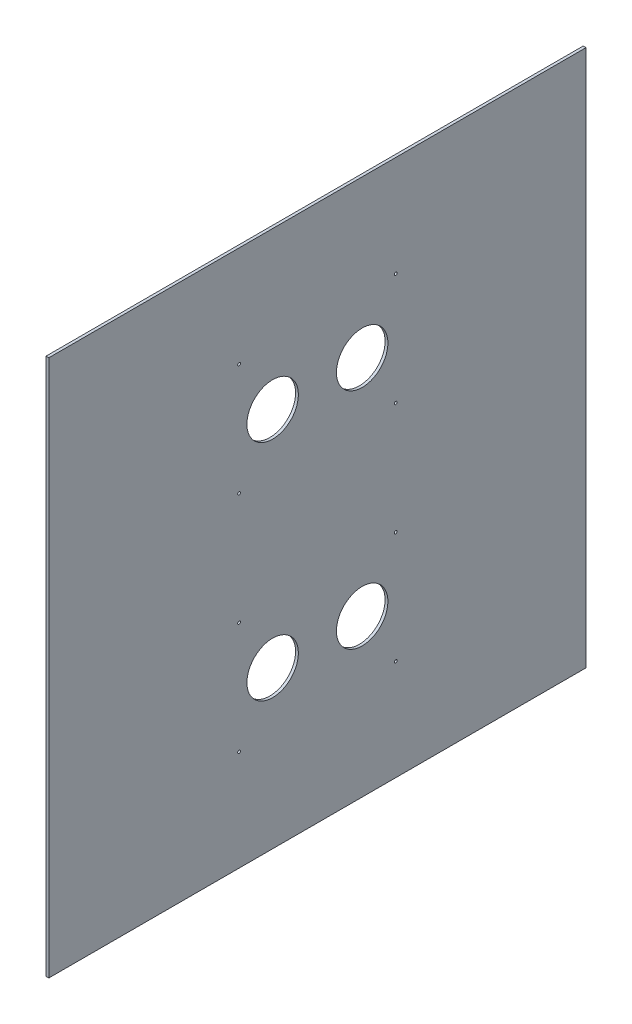
SolidWorks part; units mm, degrees
ref_plane "Front Plane" through (0, 0, 0) normal (0, 0, 1) x (1, 0, 0)
ref_plane "Top Plane" through (0, 0, 0) normal (0, 1, 0) x (1, 0, 0)
ref_plane "Right Plane" through (0, 0, 0) normal (1, 0, 0) x (0, 0, -1)
sketch "Sketch1" plane through (0, 0, 0) normal (1, 0, 0) x (0, 0, -1)
  line L1 (304.8, -304.8) -> (-304.8, -304.8)
  line L2 (304.8, -304.8) -> (304.8, 304.8)
  line L3 (304.8, 304.8) -> (-304.8, 304.8)
  line L4 (-304.8, -304.8) -> (-304.8, 304.8)
  line L5 (304.8, -304.8) -> (-304.8, 304.8) construction
  line L6 (304.8, 304.8) -> (-304.8, -304.8) construction
  point P0 (0, 0)
  dimension "D1" = 609.6
  dimension "D2" = 609.6
extrude "Boss-Extrude1" add sketch "Sketch1" along normal blind 3.175
sketch "Sketch2" plane through (3.175, 0, 0) normal (1, 0, 0) x (0, 0, -1)
  line L0 (-304.8, -304.8) -> (304.8, -304.8) construction
  line L1 (-50.8, -127) -> (50.8, -127) construction
  line L3 (-304.8, 304.8) -> (-304.8, -304.8) construction
  circle A0 centre (-50.8, -127) radius 29.21
  circle A1 centre (50.8, -127) radius 29.21
  dimension "D4" = 58.42
  dimension "D1" = 177.8
  dimension "D2" = 101.6
  dimension "D3" = 254
extrude "Cut-Extrude1" cut sketch "Sketch2" against normal through all
sketch "Sketch3" plane through (3.175, 0, 0) normal (1, 0, 0) x (0, 0, -1)
  line L0 (-88.9, -190.5) -> (88.9, -190.5) construction
  line L1 (-88.9, -63.5) -> (-88.9, -190.5) construction
  line L2 (88.9, -63.5) -> (88.9, -190.5) construction
  circle A0 centre (-88.9, -63.5) radius 1.5875
  circle A1 centre (88.9, -63.5) radius 1.5875
  circle A2 centre (-50.8, -127) radius 29.21 construction
  circle A3 centre (50.8, -127) radius 29.21 construction
  circle A4 centre (-88.9, -190.5) radius 1.5875
  circle A5 centre (88.9, -190.5) radius 1.5875
  dimension "D2" = 38.1
  dimension "D3" = 3.175
  dimension "D4" = 38.1
  dimension "D6" = 127
  dimension "D1" = 63.5
  dimension "D5" = 63.5
extrude "Cut-Extrude2" cut sketch "Sketch3" against normal through all
mirror "Mirror1" about plane through (0, 0, 0) normal (0, 1, 0) of "Cut-Extrude2", "Cut-Extrude1"
